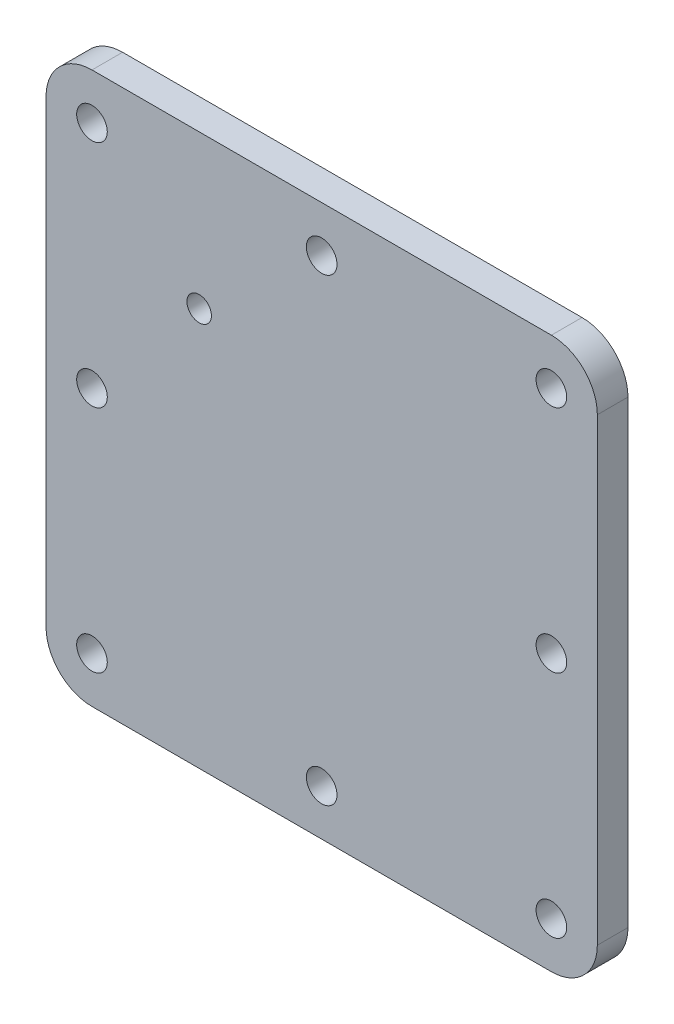
SolidWorks part; units mm, degrees
ref_plane "Front Plane" through (0, 0, 0) normal (0, 0, 1) x (1, 0, 0)
ref_plane "Top Plane" through (0, 0, 0) normal (0, 1, 0) x (1, 0, 0)
ref_plane "Right Plane" through (0, 0, 0) normal (1, 0, 0) x (0, 0, -1)
sketch "Sketch2" plane through (0, 0, 0) normal (0, 0, 1) x (1, 0, 0)
  line L0 (-75, 75) -> (75, 75) construction
  line L1 (-75, 90) -> (75, 90)
  line L2 (-90, 75) -> (-90, -75)
  line L3 (-75, -90) -> (75, -90)
  line L4 (90, 75) -> (90, -75)
  line L5 (-90, 90) -> (90, -90) construction
  line L6 (-90, -90) -> (90, 90) construction
  line L7 (75, 75) -> (75, -75) construction
  line L8 (75, -75) -> (-75, -75) construction
  line L9 (-75, -75) -> (-75, 75) construction
  line L15 (-60, 60) -> (60, -60) construction
  line L16 (-60, -60) -> (60, 60) construction
  arc A0 (-90, -75) -> (-75, -90) centre (-75, -75) ccw
  arc A1 (75, -90) -> (90, -75) centre (75, -75) ccw
  arc A2 (75, 90) -> (90, 75) centre (75, 75) cw
  arc A3 (-75, 90) -> (-90, 75) centre (-75, 75) ccw
  circle A4 centre (-75, 75) radius 5
  circle A5 centre (0, 75) radius 5
  circle A6 centre (75, 75) radius 5
  circle A7 centre (-75, 0) radius 5
  circle A8 centre (0, 0) radius 5 construction
  circle A9 centre (75, 0) radius 5
  circle A10 centre (-75, -75) radius 5
  circle A11 centre (0, -75) radius 5
  circle A12 centre (75, -75) radius 5
  point P0 (0, 0)
  dimension "D3" = 15
  dimension "D4" = 10
  dimension "D1" = 180
  dimension "D2" = 180
  dimension "D8" = 120
  dimension "D7" = 3
extrude "Boss-Extrude1" add sketch "Sketch2" along normal blind 10
sketch "Sketch3" plane through (0, 0, 10) normal (0, 0, 1) x (1, 0, 0)
  line L1 (-50, 50) -> (50, 50) construction
  line L2 (-50, 50) -> (-50, -50) construction
  line L3 (-50, -50) -> (50, -50) construction
  line L4 (50, 50) -> (50, -50) construction
  line L5 (-50, 50) -> (50, -50) construction
  line L6 (-50, -50) -> (50, 50) construction
  line L7 (0, 0) -> (-40, 0) construction
  line L8 (0, 0) -> (0, 40) construction
  line L9 (0, 40) -> (-40, 40) construction
  line L10 (-40, 0) -> (-40, 40) construction
  circle A0 centre (0, 0) radius 4 construction
  point P0 (0, 0)
  dimension "D5" = 8
  dimension "D1" = 100
  dimension "D2" = 100
  dimension "D3" = 40
  dimension "D4" = 40
sketch "Sketch4" plane through (0, 0, 10) normal (0, 0, 1) x (1, 0, 0)
  circle A0 centre (-40, 40) radius 4
  dimension "D1" = 8
extrude "Cut-Extrude1" cut sketch "Sketch4" against normal blind 10
